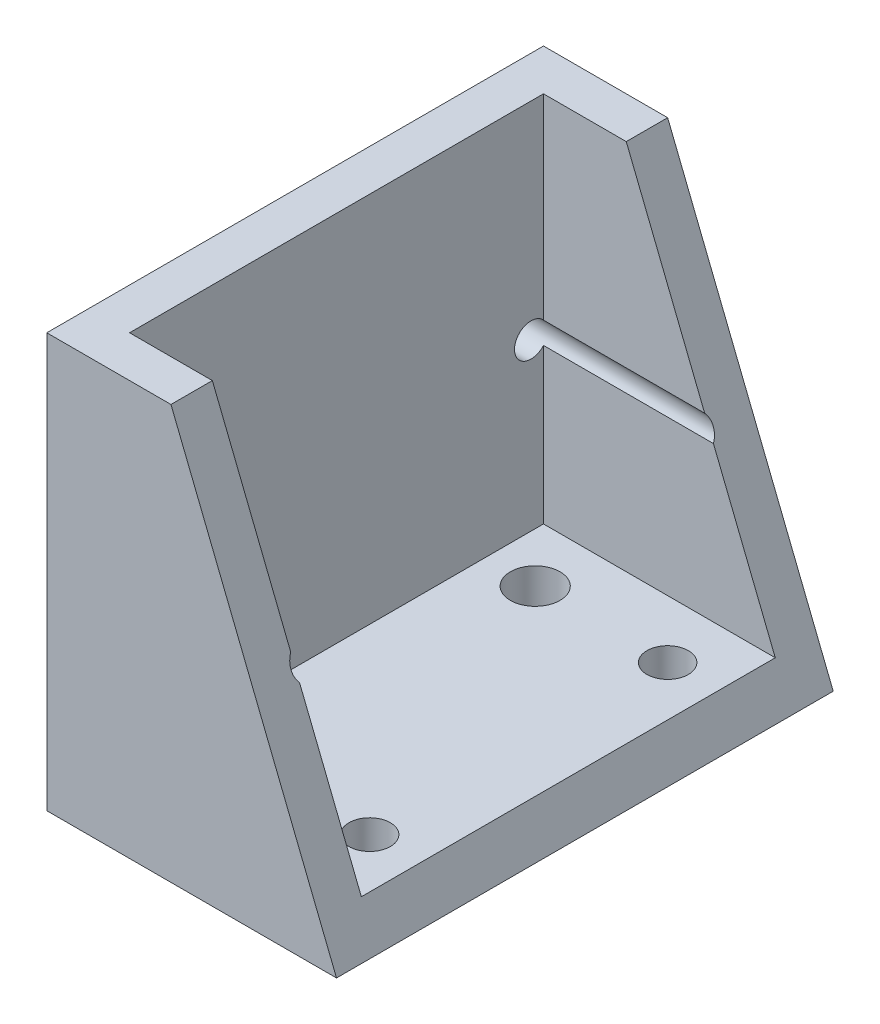
SolidWorks part; units mm, degrees
ref_plane "前视基准面" through (0, 0, 0) normal (0, 0, 1) x (1, 0, 0)
ref_plane "上视基准面" through (0, 0, 0) normal (0, 1, 0) x (1, 0, 0)
ref_plane "右视基准面" through (0, 0, 0) normal (1, 0, 0) x (0, 0, -1)
sketch "草图1" plane through (0, 0, 0) normal (0, 0, 1) x (1, 0, 0)
  line L4 (-11.3425, -7.1277) -> (-46.3425, -7.1277)
  line L5 (-46.3425, -7.1277) -> (-46.3425, 42.8723)
  line L6 (-46.3425, 42.8723) -> (-31.3425, 42.8723)
  line L7 (-31.3425, 42.8723) -> (-11.3425, -7.1277)
  dimension "D1" = 35
  dimension "D2" = 50
  dimension "D3" = 15
extrude "凸台-拉伸1" add sketch "草图1" along normal blind 60
sketch "草图2" plane through (0, 42.8723, 0) normal (0, 1, 0) x (1, 0, 0)
  line L0 (-41.3425, -5) -> (-6.8445, -5)
  line L1 (-6.8445, -5) -> (-6.8445, -55)
  line L2 (-6.8445, -55) -> (-41.3425, -55)
  line L3 (-41.3425, -55) -> (-41.3425, -5)
  line L4 (-46.3425, -60) -> (-46.3425, 0) construction
  line L5 (-31.3425, 0) -> (-46.3425, 0) construction
  line L6 (-31.3425, -60) -> (-46.3425, -60) construction
  dimension "D1" = 5
  dimension "D2" = 5
  dimension "D3" = 5
extrude "切除-拉伸1" cut sketch "草图2" against normal blind 45
sketch "草图3" plane through (0, -7.1277, 0) normal (0, -1, 0) x (1, 0, 0)
  line L0 (-28.8425, 60) -> (-28.8425, -8.8482) construction
  line L1 (-46.3425, 60) -> (-11.3425, 60) construction
  line L2 (-46.3425, 30) -> (-1.4335, 30) construction
  line L3 (-46.3425, 60) -> (-46.3425, 0) construction
  circle A0 centre (-35.3425, 48) radius 3
  circle A11 centre (-35.3425, 12) radius 3
  circle A12 centre (-19.3425, 12) radius 2.5
  circle A13 centre (-19.3425, 48) radius 2.5
  dimension "D1" = 6
  dimension "D5" = 16
  dimension "D2" = 11
  dimension "D3" = 18
  dimension "D4" = 16
extrude "切除-拉伸2" cut sketch "草图3" against normal through all
sketch "草图6" plane through (-46.3425, 0, 0) normal (-1, 0, 0) x (0, 0, 1)
  line L0 (30, 42.8723) -> (30, -36.0381) construction
  line L1 (60, 42.8723) -> (0, 42.8723) construction
  line L2 (60, 17.8723) -> (-3.6113, 17.8723) construction
  line L3 (60, 42.8723) -> (60, -7.1277) construction
  circle A0 centre (53.5, 17.8723) radius 2
  circle A1 centre (6.5, 17.8723) radius 2
  dimension "D1" = 4
  dimension "D2" = 47
extrude "切除-拉伸3" cut sketch "草图6" against normal through all
